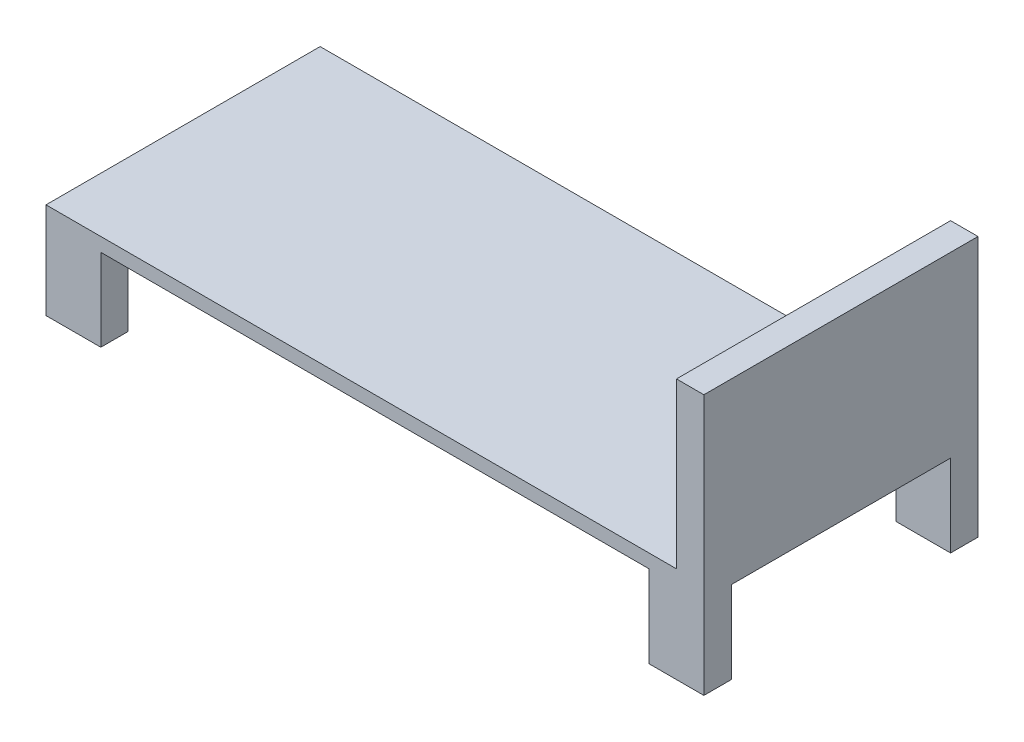
SolidWorks part; units mm, degrees
material "Balsa"
ref_plane "Front Plane" through (0, 0, 0) normal (0, 0, 1) x (1, 0, 0)
ref_plane "Top Plane" through (0, 0, 0) normal (0, 1, 0) x (1, 0, 0)
ref_plane "Right Plane" through (0, 0, 0) normal (1, 0, 0) x (0, 0, -1)
sketch "Sketch1" plane through (0, 0, 0) normal (0, 1, 0) x (1, 0, 0)
  line L1 (0, 0) -> (1219.2, 0)
  line L2 (0, 0) -> (0, 508)
  line L3 (0, 508) -> (1219.2, 508)
  line L4 (1219.2, 0) -> (1219.2, 508)
extrude "Boss-Extrude1" add sketch "Sketch1" along normal blind 25.4
sketch "Sketch2" plane through (0, 25.4, 0) normal (0, 1, 0) x (1, 0, 0)
  line L5 (0, 0) -> (1219.2, 0) construction
  line L6 (1219.2, 508) -> (1168.4, 508)
  line L7 (1219.2, 508) -> (1219.2, 0)
  line L8 (1219.2, 0) -> (1168.4, 0)
  line L9 (1168.4, 508) -> (1168.4, 0)
  dimension "D1" = 50.8
extrude "Boss-Extrude2" add sketch "Sketch2" along normal blind 304.8
sketch "Sketch3" plane through (0, 0, 0) normal (0, -1, 0) x (1, 0, 0)
  line L1 (0, 0) -> (101.6, 0)
  line L2 (0, 0) -> (0, -50.8)
  line L3 (0, -50.8) -> (101.6, -50.8)
  line L4 (101.6, 0) -> (101.6, -50.8)
  line L5 (0, -508) -> (101.6, -508)
  line L6 (0, -508) -> (0, -457.2)
  line L7 (0, -457.2) -> (101.6, -457.2)
  line L8 (101.6, -508) -> (101.6, -457.2)
  line L9 (1219.2, 0) -> (1117.6, 0)
  line L10 (1219.2, 0) -> (1219.2, -50.8)
  line L11 (1219.2, -50.8) -> (1117.6, -50.8)
  line L12 (1117.6, 0) -> (1117.6, -50.8)
  line L13 (1219.2, -508) -> (1117.6, -508)
  line L14 (1219.2, -508) -> (1219.2, -457.2)
  line L15 (1219.2, -457.2) -> (1117.6, -457.2)
  line L16 (1117.6, -508) -> (1117.6, -457.2)
extrude "Boss-Extrude3" add sketch "Sketch3" along normal blind 152.4
